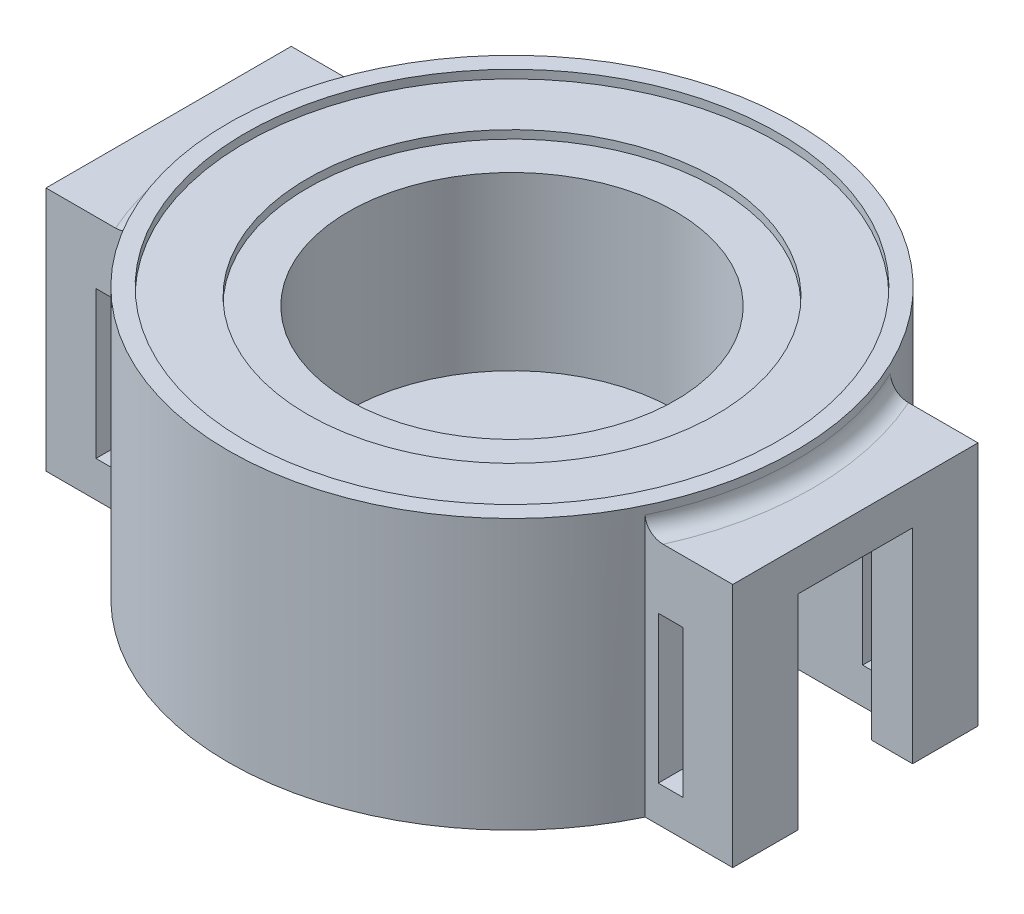
SolidWorks part; units mm, degrees
other "Markup1"
sketch "Sketch6" plane through (-53.34, 0, 46.5455) normal (-0.405, -0.8991, 0.1661) x (-0.8101, 0.2686, -0.5212)
ref_plane "Front Plane" through (0, 0, 0) normal (0, 0, 1) x (1, 0, 0)
ref_plane "Top Plane" through (0, 0, 0) normal (0, 1, 0) x (1, 0, 0)
ref_plane "Right Plane" through (0, 0, 0) normal (1, 0, 0) x (0, 0, -1)
sketch "Sketch1" plane through (0, 0, 0) normal (0, 1, 0) x (1, 0, 0)
  circle A1 centre (0, 0) radius 44.069
  dimension "D1" = 88.138
extrude "Boss-Extrude1" add sketch "Sketch1" along normal blind 40.64
sketch "Sketch2" plane through (0, 40.64, 0) normal (0, 1, 0) x (1, 0, 0)
  circle A1 centre (0, 0) radius 44.069 construction
  circle A4 centre (0, 0) radius 41.402
  circle A5 centre (0, 0) radius 44.069
  dimension "D2" = 82.804
extrude "Boss-Extrude2" add sketch "Sketch2" along normal blind 1.2954
sketch "Sketch3" plane through (0, 0, 0) normal (0, 1, 0) x (1, 0, 0)
  line L0 (0, -61.5189) -> (0, 50.453) construction
  line L1 (-53.34, 19.05) -> (-53.34, -19.05)
  line L2 (-53.34, -19.05) -> (-39.7388, -19.05)
  line L3 (-53.34, 19.05) -> (-39.7388, 19.05)
  line L4 (53.34, 19.05) -> (53.34, -19.05)
  line L5 (53.34, 19.05) -> (39.7388, 19.05)
  line L6 (53.34, -19.05) -> (39.7388, -19.05)
  circle A0 centre (0, 0) radius 44.069 construction
  arc A1 (39.7388, -19.05) -> (39.7388, 19.05) centre (0, 0) ccw
  arc A2 (-39.7388, 19.05) -> (-39.7388, -19.05) centre (0, 0) ccw
  arc A3 (39.7388, 19.05) -> (39.7388, -19.05) centre (0, 0) cw
  point P8 (-53.34, 0)
  dimension "D1" = 38.1
  dimension "D2" = 53.34
extrude "Boss-Extrude3" add sketch "Sketch3" along normal blind 38.1 contours A1 L6 L4 L5 | A2 L3 L1 L2
sketch "Sketch4" plane through (0, 0, 0) normal (0, 1, 0) x (1, 0, 0)
  line L0 (0, -34.2481) -> (0, 43.0478) construction
  line L1 (-53.34, -8.89) -> (-53.34, 8.89)
  line L2 (-53.34, 19.05) -> (-53.34, -19.05) construction
  line L3 (-53.34, 8.89) -> (-46.99, 8.89)
  line L4 (-46.99, 8.89) -> (-46.99, 12.7)
  line L5 (-46.99, 12.7) -> (-31.75, 12.7)
  line L6 (-31.75, 12.7) -> (-31.75, -12.7)
  line L7 (-31.75, -12.7) -> (-46.99, -12.7)
  line L8 (-46.99, -12.7) -> (-46.99, -8.89)
  line L9 (-46.99, -8.89) -> (-53.34, -8.89)
  line L10 (-53.34, -19.05) -> (-39.7388, -19.05) construction
  line L11 (-53.34, 19.05) -> (-39.7388, 19.05) construction
  line L12 (46.99, -12.7) -> (46.99, -8.89)
  line L13 (31.75, -12.7) -> (46.99, -12.7)
  line L14 (31.75, 12.7) -> (31.75, -12.7)
  line L15 (46.99, 12.7) -> (31.75, 12.7)
  line L16 (46.99, 8.89) -> (46.99, 12.7)
  line L17 (53.34, 8.89) -> (46.99, 8.89)
  line L18 (53.34, -8.89) -> (53.34, 8.89)
  line L19 (46.99, -8.89) -> (53.34, -8.89)
  point P17 (-53.34, 0)
  dimension "D1" = 6.35
  dimension "D2" = 6.35
  dimension "D3" = 6.35
  dimension "D4" = 17.78
  dimension "D5" = 21.59
extrude "Cut-Extrude1" cut sketch "Sketch4" along normal blind 31.75
sketch "Sketch5" plane through (0, 0, -19.05) normal (0, 0, -1) x (-1, 0, 0)
  line L0 (0, 0) -> (0, 34.6993) construction
  line L2 (41.7708, 5.588) -> (45.5808, 5.588)
  line L3 (41.7708, 5.588) -> (41.7708, 28.448)
  line L4 (41.7708, 28.448) -> (45.5808, 28.448)
  line L5 (45.5808, 5.588) -> (45.5808, 28.448)
  line L7 (31.75, 31.75) -> (46.99, 31.75) construction
  line L8 (-41.7708, 28.448) -> (-45.5808, 28.448)
  line L9 (-45.5808, 5.588) -> (-45.5808, 28.448)
  line L10 (-41.7708, 5.588) -> (-45.5808, 5.588)
  line L11 (-41.7708, 5.588) -> (-41.7708, 28.448)
  point P9 (43.6758, 5.588)
  dimension "D1" = 3.81
  dimension "D2" = 22.86
  dimension "D3" = 3.302
  dimension "D4" = 3.937
extrude "Cut-Extrude2" cut sketch "Sketch5" against normal through all
fillet "Fillet1" radius 2.54 2 edges at (-44.069, 38.1, 0) (44.069, 38.1, 0)
sketch "Sketch7" plane through (0, 40.64, 0) normal (0, 1, 0) x (1, 0, 0)
  circle A0 centre (0, 0) radius 25.4
  dimension "D1" = 50.8
extrude "Cut-Extrude3" cut sketch "Sketch7" against normal blind 27.94
sketch "Sketch8" plane through (0, 0, 0) normal (0, -1, 0) x (1, 0, 0)
  circle A0 centre (0, 0) radius 11.43
  dimension "D1" = 22.86
extrude "Cut-Extrude4" cut sketch "Sketch8" against normal through all
sketch "Sketch9" plane through (0, 40.64, 0) normal (0, 1, 0) x (1, 0, 0)
  circle A0 centre (0, 0) radius 31.75
  dimension "D1" = 63.5
extrude "Cut-Extrude5" cut sketch "Sketch9" against normal blind 1.27
